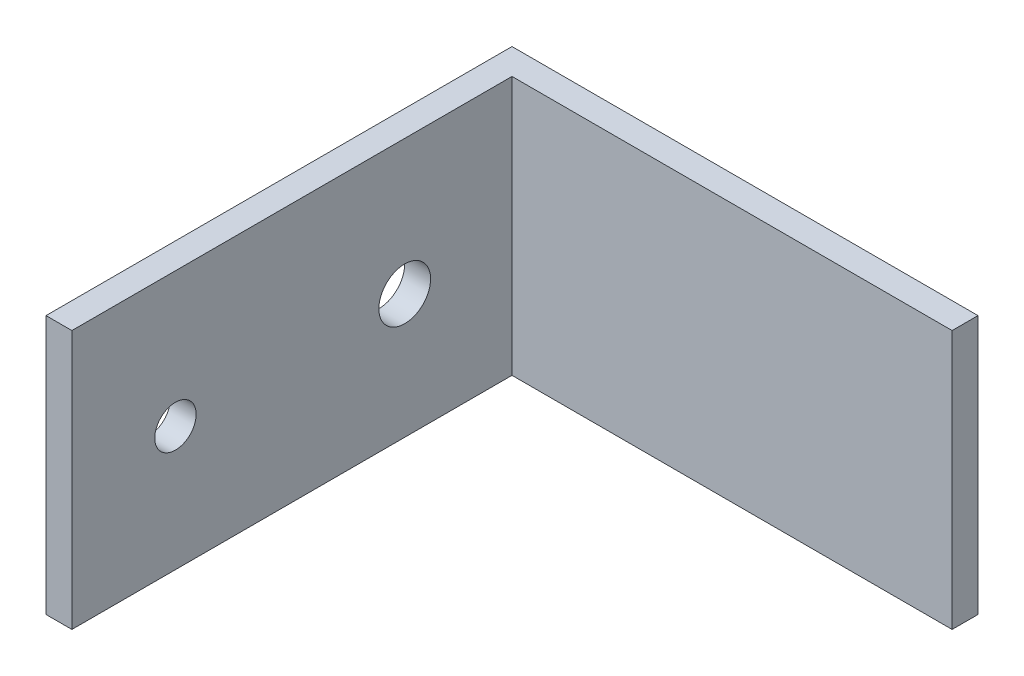
SolidWorks part; units mm, degrees
ref_plane "Front Plane" through (0, 0, 0) normal (0, 0, 1) x (1, 0, 0)
ref_plane "Top Plane" through (0, 0, 0) normal (0, 1, 0) x (1, 0, 0)
ref_plane "Right Plane" through (0, 0, 0) normal (1, 0, 0) x (0, 0, -1)
sketch "Sketch1" plane through (0, 0, 0) normal (0, 0, 1) x (1, 0, 0)
  line L1 (0, 0) -> (85, 0)
  line L2 (0, 0) -> (0, -50)
  line L3 (0, -50) -> (85, -50)
  line L4 (85, 0) -> (85, -50)
  dimension "D1" = 85
  dimension "D2" = 50
extrude "Boss-Extrude1" add sketch "Sketch1" along normal blind 5
sketch "Sketch2" plane through (0, 0, 0) normal (-1, 0, 0) x (0, 0, 1)
  line L0 (5, -50) -> (0, -50) construction
  line L1 (0, 0) -> (90, 0)
  line L2 (0, 0) -> (0, -50)
  line L3 (0, -50) -> (90, -50)
  line L4 (90, 0) -> (90, -50)
  dimension "D1" = 90
extrude "Boss-Extrude2" add sketch "Sketch2" along normal blind 5
sketch "Sketch3" plane through (-5, 0, 0) normal (-1, 0, 0) x (0, 0, 1)
  line L1 (0, -50) -> (90, -50) construction
  line L2 (90, -50) -> (90, 0) construction
  line L3 (70, -26) -> (25.72, -26) construction
  circle A0 centre (70, -26) radius 4
  circle A1 centre (25.72, -26) radius 5
  dimension "D1" = 24
  dimension "D2" = 8
  dimension "D5" = 10
  dimension "D3" = 20
  dimension "D4" = 44.28
extrude "Cut-Extrude1" cut sketch "Sketch3" against normal blind 5
